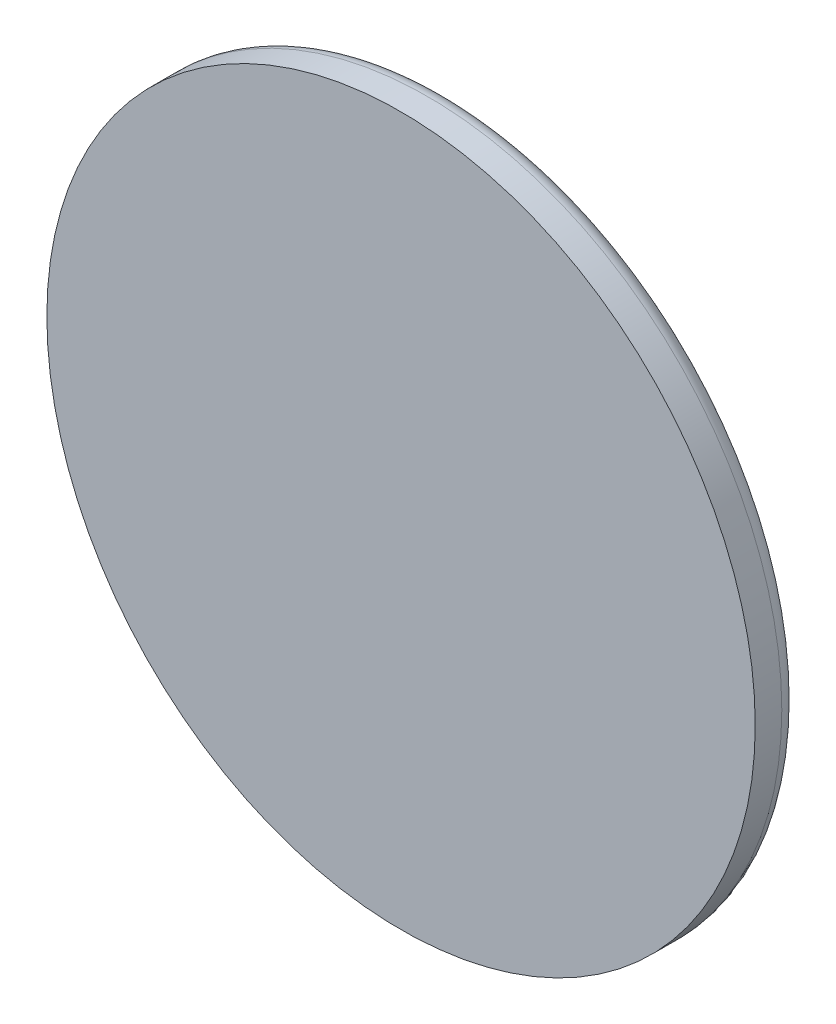
SolidWorks part; units mm, degrees
ref_plane "Front Plane" through (0, 0, 0) normal (0, 0, 1) x (1, 0, 0)
ref_plane "Top Plane" through (0, 0, 0) normal (0, 1, 0) x (1, 0, 0)
ref_plane "Right Plane" through (0, 0, 0) normal (1, 0, 0) x (0, 0, -1)
sketch "Sketch1" plane through (0, 0, 0) normal (0, 0, 1) x (1, 0, 0)
  circle A0 centre (-13.18, 8.4476) radius 40
  dimension "D1" = 80
extrude "Boss-Extrude1" add sketch "Sketch1" along normal blind 5
fillet "Fillet2" radius 2 1 edges at (26.82, 8.4476, 0)
